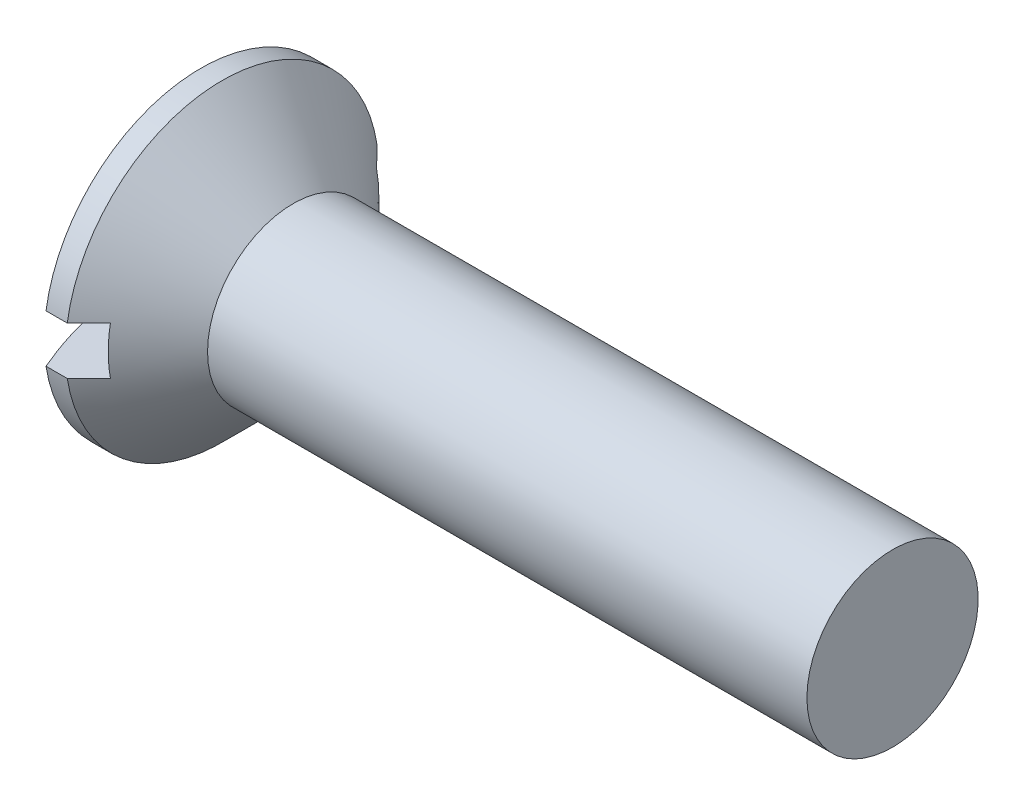
SolidWorks part; units mm, degrees
revolve "Base-Revolve" add sketch "BodySke" angle 360 about L4
sketch "BodySke" plane through (0, 0, 0) normal (0, 0, 1) x (1, 0, 0)
  line L0 (0, 0) -> (42.2988, 0)
  line L1 (42.2988, 0) -> (42.2988, 5)
  line L2 (42.2988, 5) -> (7.2988, 5)
  line L3 (7.2988, 5) -> (-0.5742, 12.873) construction
  line L4 (-15.875, 0) -> (82.55, 0) construction
  line L5 (7.2988, -5) -> (-0.5742, -12.873) construction
  line L6 (8.7988, 8.175) -> (8.7988, -7.7) construction
  line L7 (2.2988, 5.2375) -> (2.2988, -10.6375) construction
  line L8 (7.2988, 5) -> (3.1488, 9.15)
  line L9 (3.1488, 9.15) -> (1.9074, 9.15)
  arc A0 (0, 0) -> (1.9074, 9.15) centre (22.9, 0) cw
  arc A1 (2.2988, 10) -> (0, 0) centre (22.9, 0) ccw construction
  dimension "Crown_rad" = 22.9
  dimension "Diameter" = 10
  dimension "Advance" = 1.5
  dimension "Thread_nom" = 40
  dimension "Head_ang" = 90
  dimension "D3" = 20
  dimension "Side_ht" = 5
  dimension "D4" = 2.2988
  dimension "Length" = 40
  dimension "Head_dia" = 18.3
cosmetic thread "ThreadCosmetic" [suppressed] parameters "Thread_length"=33.5, "Thread_minor"=8.344
ref_plane "Plane1" through (0, 0, 0) normal (0, 0, 1) x (1, 0, 0)
ref_plane "Plane2" through (0, 0, 0) normal (0, 1, 0) x (1, 0, 0)
ref_plane "Plane3" through (0, 0, 0) normal (1, 0, 0) x (0, 0, -1)
sketch "Sketch2" plane through (0, 0, 0) normal (1, 0, 0) x (0, 0, -1)
  line L0 (9.15, -1.4) -> (-9.15, -1.4)
  line L1 (9.15, -1.4) -> (9.15, 1.4)
  line L2 (-9.15, 1.4) -> (9.15, 1.4)
  line L3 (-9.15, 1.4) -> (-9.15, -1.4)
  dimension "D1" = 18.3
  dimension "Slot_width" = 2.8
  dimension "D3" = 9.15
  dimension "D4" = 1.4
extrude "Slot" cut sketch "Sketch2" along normal blind 4.4
sketch "Sketch3" plane through (0, 0, 0) normal (1, 0, 0) x (0, 0, -1)
  line L0 (1.085, -5.62) -> (-1.085, -5.62)
  line L1 (1.085, -5.62) -> (1.085, 5.62)
  line L2 (-1.085, 5.62) -> (1.085, 5.62)
  line L3 (-1.085, 5.62) -> (-1.085, -5.62)
  dimension "Cross_width" = 2.17
  dimension "D1" = 1.085
  dimension "Cross_dia" = 11.24
  dimension "D2" = 5.62
ref_plane "Plane4" through (7.15, 0, 0) normal (1, 0, 0) x (0, 0, -1)
sketch "Sketch4" plane through (7.15, 0, 0) normal (1, 0, 0) x (0, 0, -1)
  line L0 (0.5425, -0.5425) -> (-0.5425, -0.5425)
  line L1 (0.5425, -0.5425) -> (0.5425, 0.5425)
  line L2 (-0.5425, 0.5425) -> (0.5425, 0.5425)
  line L3 (-0.5425, 0.5425) -> (-0.5425, -0.5425)
  dimension "D1" = 1.085
  dimension "D2" = 1.085
  dimension "D3" = 0.5425
  dimension "D4" = 0.5425
loft "Cross" cut profiles "Sketch3", "Sketch4"
pattern_circular "CirPattern1" count 2 every 90 about axis through (0, 0, 0) along (1, 0, 0) of "Cross"
sketch "ThdSchSke" plane through (0, 0, 0) normal (0, 0, 1) x (1, 0, 0)
  line L0 (8.7988, -4.172) -> (8.219, -5)
  line L1 (8.7988, -4.172) -> (9.3786, -5)
  line L2 (9.3786, -5) -> (9.3786, -6.25)
  line L3 (-3.175, 0) -> (5.1513, 0) construction
  line L5 (9.3786, -6.25) -> (8.219, -6.25)
  line L6 (8.219, -6.25) -> (8.219, -5)
  line L8 (42.2988, -5) -> (42.2988, 5) construction
  dimension "Diameter" = 10
  dimension "Thread_minor" = 8.344
  dimension "Start" = 33.5
revolve "ThreadSchematic" [suppressed] cut sketch "ThdSchSke" angle 360 about L3
pattern_linear "ThdSchPat" [suppressed]
equation "\"D1@Sketch2\" = \"Head_dia@BodySke\""
equation "\"D3@Sketch2\" = \"D1@Sketch2\" / 2"
equation "\"D4@Sketch2\" = \"Slot_width@Sketch2\" / 2"
equation "\"D1@Sketch3\" = \"Cross_width@Sketch3\" / 2"
equation "\"D2@Sketch3\" = \"Cross_dia@Sketch3\" / 2"
equation "\"D1@Sketch4\" = \"Cross_width@Sketch3\"*.5"
equation "\"D2@Sketch4\" = \"D1@Sketch4\""
equation "\"D3@Sketch4\" = \"D1@Sketch4\" / 2"
equation "\"D4@Sketch4\" = \"D2@Sketch4\" / 2"
equation "\"Thread_length@ThreadCosmetic\" = ((sgn( (\"Length@BodySke\" - \"Advance@BodySke\" - \"Side_ht@BodySke\" ) - \"Thread_nom@BodySke\" )-1)*( (\"Length@BodySke\" - \"Advance@BodySke\" - \"Side_ht@BodySke\" ) - \"Thread_nom@BodySke\" ))/-2+ \"Thread_nom@BodySke\""
equation "\"Thread_minor@ThdSchSke\" = \"Thread_minor@ThreadCosmetic\""
equation "\"Diameter@ThdSchSke\" = \"Diameter@BodySke\""
equation "\"Overcut@ThdSchSke\" = \"Diameter@BodySke\" * 1.25"
equation "\"Start@ThdSchSke\" =  \"Thread_length@ThreadCosmetic\""
equation "\"Num_threads@ThdSchPat\" = int( \"Thread_length@ThreadCosmetic\" / \"Advance@BodySke\" + 0.999 )  + 1"
equation "\"Advance@ThdSchPat\" = \"Thread_length@ThreadCosmetic\" /  (\"Num_threads@ThdSchPat\" - 1) 'relax it"
